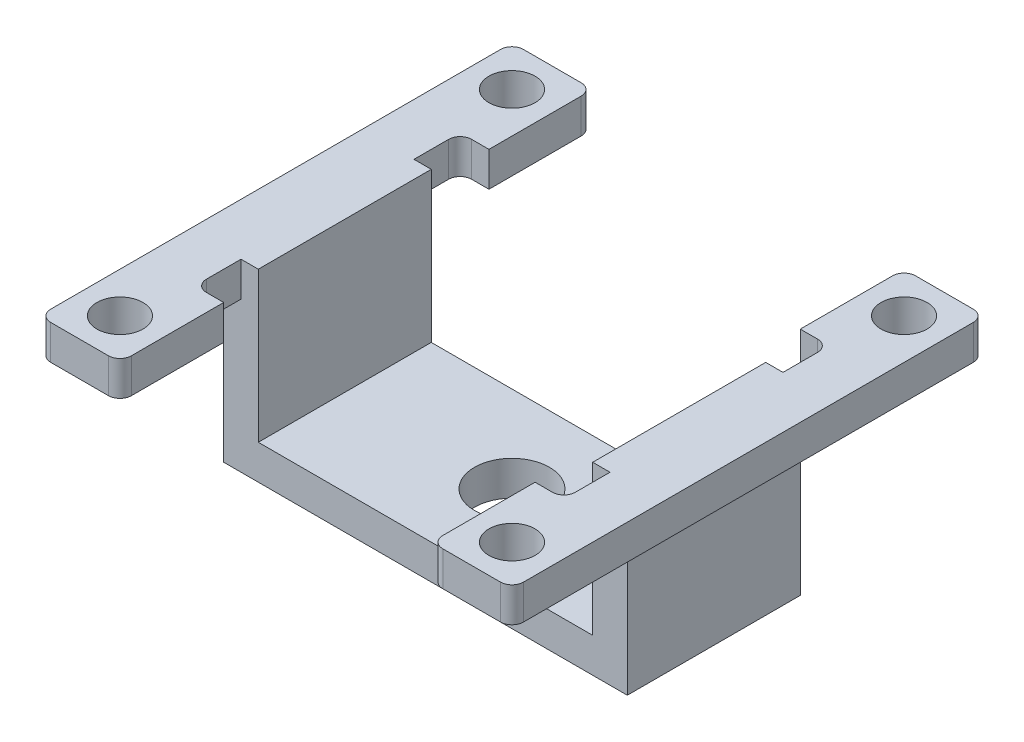
SolidWorks part; units mm, degrees
ref_plane "前视基准面" through (0, 0, 0) normal (0, 0, 1) x (1, 0, 0)
ref_plane "上视基准面" through (0, 0, 0) normal (0, 1, 0) x (1, 0, 0)
ref_plane "右视基准面" through (0, 0, 0) normal (1, 0, 0) x (0, 0, -1)
sketch "草图1" plane through (0, 0, 0) normal (0, 1, 0) x (1, 0, 0)
  line L0 (0, 0) -> (0, 50000) construction
  line L1 (-12.5, 7.5) -> (12.5, 7.5)
  line L3 (-12.5, -7.5) -> (12.5, -7.5)
  line L5 (-12.5, 7.5) -> (12.5, -7.5) construction
  line L6 (-12.5, -7.5) -> (12.5, 7.5) construction
  line L7 (12.5, -7.5) -> (17.5, -7.5)
  line L8 (-12.5, 7.5) -> (-17.5, 7.5)
  line L10 (-12.5, -7.5) -> (-17.5, -7.5)
  line L11 (-17.5, 7.5) -> (-17.5, -7.5)
  line L12 (17.5, 7.5) -> (17.5, -7.5)
  line L13 (12.5, 7.5) -> (17.5, 7.5)
  circle A0 centre (0, 0) radius 3.25
  point P0 (0, 0)
  dimension "D3" = 6.5
  dimension "D1" = 15
  dimension "D2" = 25
  dimension "D4" = 5
extrude "凸台-拉伸1" add sketch "草图1" along normal blind 3
sketch "草图2" plane through (0, 3, 0) normal (0, 1, 0) x (1, 0, 0)
  line L0 (-17.5, -7.5) -> (17.5, -7.5) construction
  line L1 (-17.5, 7.5) -> (-14.5, 7.5)
  line L2 (-17.5, 7.5) -> (-17.5, -7.5)
  line L3 (-17.5, -7.5) -> (-14.5, -7.5)
  line L4 (-14.5, 7.5) -> (-14.5, -7.5)
  line L6 (17.5, 7.5) -> (14.5, 7.5)
  line L7 (17.5, 7.5) -> (17.5, -7.5)
  line L8 (17.5, -7.5) -> (14.5, -7.5)
  line L9 (14.5, 7.5) -> (14.5, -7.5)
  dimension "D1" = 3
  dimension "D2" = 3
extrude "凸台-拉伸2" add sketch "草图2" along normal blind 10
sketch "草图3" plane through (0, 13, 0) normal (0, 1, 0) x (1, 0, 0)
  line L0 (0, 0) -> (0, 50000) construction
  line L1 (-15, -11.5) -> (-13.5, -11.5)
  line L3 (0, 0) -> (-50000, 0) construction
  line L4 (-13.5, 18.5) -> (-13.5, 11.5)
  line L14 (-13.5, -17.5) -> (-13.5, -19.5)
  line L15 (-14.5, -20.5) -> (-19.5, -20.5)
  line L16 (-20.5, -19.5) -> (-20.5, 19.5)
  line L17 (-14.5, 7.5) -> (-14.5, -7.5)
  line L18 (-14.5, -7.5) -> (-14.5, 7.5) construction
  line L19 (-14.5, -7.5) -> (14.5, -7.5) construction
  line L20 (-14.5, -7.5) -> (-16, -7.5)
  line L21 (-17.5, -7.5) -> (-14.5, -7.5) construction
  line L22 (-16, -7.5) -> (-16, -10.5)
  line L23 (-16, 7.5) -> (-16, 10.5)
  line L24 (-14.5, 7.5) -> (-16, 7.5)
  line L25 (-14.5, 20.5) -> (-19.5, 20.5)
  line L26 (-13.5, 18.5) -> (-13.5, 19.5)
  line L29 (-15, 11.5) -> (-13.5, 11.5)
  line L30 (14.5, 7.5) -> (16, 7.5)
  line L31 (14.5, 7.5) -> (14.5, -7.5)
  line L32 (14.5, -7.5) -> (16, -7.5)
  line L33 (16, -7.5) -> (16, -10.5)
  line L34 (15, -11.5) -> (13.5, -11.5)
  line L37 (13.5, -18.5) -> (13.5, -19.5)
  line L38 (14.5, -20.5) -> (19.5, -20.5)
  line L39 (20.5, -19.5) -> (20.5, 19.5)
  line L40 (14.5, 20.5) -> (19.5, 20.5)
  line L41 (13.5, 18.5) -> (13.5, 19.5)
  line L44 (15, 11.5) -> (13.5, 11.5)
  line L45 (16, 7.5) -> (16, 10.5)
  line L46 (13.5, 18.5) -> (13.5, 11.5)
  line L47 (13.5, -18.5) -> (13.5, -11.5)
  line L48 (-13.5, -17.5) -> (-13.5, -11.5)
  circle A5 centre (-17, 17) radius 2
  circle A6 centre (17, 17) radius 2
  circle A7 centre (17, -17) radius 2
  circle A8 centre (-17, -17) radius 2
  arc A9 (20.5, 19.5) -> (19.5, 20.5) centre (19.5, 19.5) ccw
  arc A10 (14.5, 20.5) -> (13.5, 19.5) centre (14.5, 19.5) ccw
  arc A11 (15, 11.5) -> (16, 10.5) centre (15, 10.5) cw
  arc A15 (-19.5, 20.5) -> (-20.5, 19.5) centre (-19.5, 19.5) ccw
  arc A16 (-14.5, 20.5) -> (-13.5, 19.5) centre (-14.5, 19.5) cw
  arc A20 (-16, 10.5) -> (-15, 11.5) centre (-15, 10.5) cw
  arc A21 (16, -10.5) -> (15, -11.5) centre (15, -10.5) cw
  arc A23 (19.5, -20.5) -> (20.5, -19.5) centre (19.5, -19.5) ccw
  arc A24 (13.5, -19.5) -> (14.5, -20.5) centre (14.5, -19.5) ccw
  arc A27 (-19.5, -20.5) -> (-20.5, -19.5) centre (-19.5, -19.5) cw
  arc A28 (-13.5, -19.5) -> (-14.5, -20.5) centre (-14.5, -19.5) cw
  arc A29 (-16, -10.5) -> (-15, -11.5) centre (-15, -10.5) ccw
  point P41 (-14.5, 0)
  point P42 (-20.5, 0)
  point P64 (20.5, 20.5)
  point P67 (13.5, 20.5)
  point P70 (16, 11.5)
  point P73 (12, 11.5)
  point P76 (14.5, 16.5)
  point P79 (12, 16.5)
  point P82 (-20.5, 20.5)
  point P85 (-13.5, 20.5)
  point P88 (-14.5, 16.5)
  point P91 (-12, 16.5)
  point P94 (-12, 11.5)
  point P97 (-16, 11.5)
  point P100 (16, -11.5)
  point P103 (12, -11.5)
  point P106 (20.5, -20.5)
  point P109 (13.5, -20.5)
  point P112 (14.5, -16.5)
  point P115 (12, -16.5)
  point P118 (-20.5, -20.5)
  point P121 (-13.5, -20.5)
  point P124 (-16, -11.5)
  point P127 (-12, -11.5)
  point P130 (-12, -16.5)
  point P133 (-14.5, -16.5)
  dimension "D7" = 4
  dimension "D13" = 1
  dimension "D5" = 34
  dimension "D6" = 34
  dimension "D10" = 3.5
  dimension "D11" = 3.5
  dimension "D12" = 3.5
extrude "凸台-拉伸3" add sketch "草图3" along normal blind 3
sketch "草图5" plane through (0, 0, 0) normal (0, 0, 1) x (1, 0, 0)
  line L0 (0, 0) -> (0, 50000) construction
  line L3 (0, 0) -> (-50000, 0) construction
  line L5 (-23.5, 25) -> (-9.5, 25)
  line L6 (-23.5, 25) -> (-23.5, -25)
  line L7 (-23.5, -25) -> (-9.5, -25)
  line L8 (-9.5, 25) -> (-9.5, -25)
  line L9 (23.5, -25) -> (9.5, -25)
  line L10 (9.5, 25) -> (9.5, -25)
  line L11 (23.5, 25) -> (9.5, 25)
  line L12 (23.5, 25) -> (23.5, -25)
  circle A0 centre (-14, -14) radius 1.25
  circle A2 centre (14, -14) radius 1.25
  circle A3 centre (14, 14) radius 1.25
  circle A4 centre (-14, 14) radius 1.25
  circle A5 centre (-17, 19.5) radius 2
  circle A6 centre (17, 19.5) radius 2
  circle A7 centre (17, -19.5) radius 2
  circle A8 centre (-17, -19.5) radius 2
  dimension "D3" = 2.5
  dimension "D7" = 4
  dimension "D1" = 28
  dimension "D2" = 28
  dimension "D4" = 50
  dimension "D5" = 34
  dimension "D6" = 39
  dimension "D8" = 14
